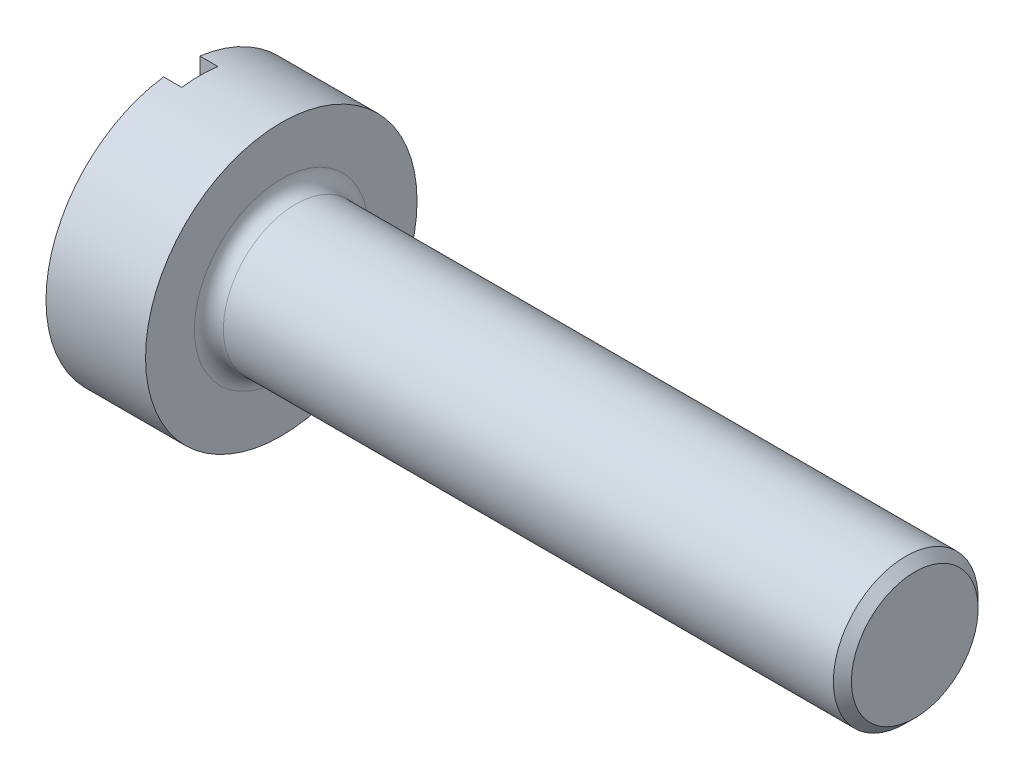
SolidWorks part; units mm, degrees
ref_plane "Front Plane" through (0, 0, 0) normal (0, 0, 1) x (1, 0, 0)
ref_plane "Top Plane" through (0, 0, 0) normal (0, 1, 0) x (1, 0, 0)
ref_plane "Right Plane" through (0, 0, 0) normal (1, 0, 0) x (0, 0, -1)
sketch "Sketch1" plane through (0, 0, 0) normal (0, 0, 1) x (1, 0, 0)
  line L0 (0, 0) -> (0, 1.5)
  line L1 (0, 1.5) -> (1.1, 1.5)
  line L2 (1.1, 1.5) -> (1.1, 0)
  line L3 (0, 0) -> (8.1, 0)
  line L4 (8.1, 0) -> (8.1, 0.8)
  line L5 (8.1, 0.8) -> (1.1, 0.8)
  dimension "D1" = 1.5
  dimension "D2" = 1.1
  dimension "D3" = 7
revolve "Revolve1" add sketch "Sketch1" angle 360 about L3
chamfer "Chamfer1" distance 0.1 angle 45 1 edges at (8.1, 0, 0.8)
fillet "Fillet1" radius 0.16 1 edges at (1.1, 0, 0.8)
sketch "Sketch2" plane through (0, 0, 0) normal (0, 1, 0) x (1, 0, 0)
  line L1 (0, 0) -> (0.2, 0)
  line L2 (0, 0) -> (0, 0.2)
  line L3 (0, 0.2) -> (0.2, 0.2)
  line L4 (0.2, 0) -> (0.2, 0.2)
  line L5 (0, 0) -> (0.2, 0)
  line L6 (0, 0) -> (0, -0.2)
  line L7 (0, -0.2) -> (0.2, -0.2)
  line L8 (0.2, 0) -> (0.2, -0.2)
extrude "Extrude1" cut sketch "Sketch2" against normal through all both and the other way through all contours L8 L1 L6 L7 | L1 L4 L3 L2
